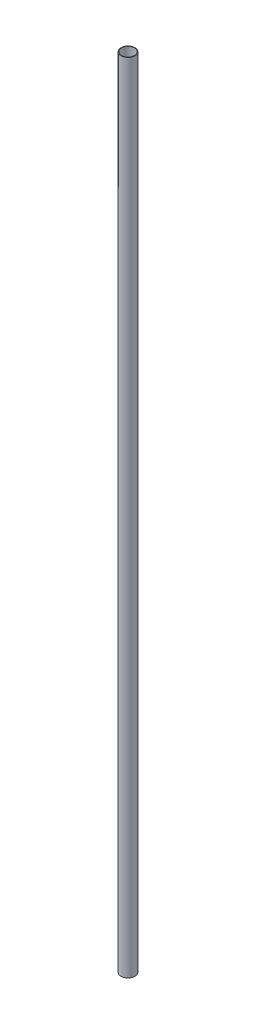
SolidWorks part; units mm, degrees
ref_plane "Front Plane" through (0, 0, 0) normal (0, 0, 1) x (1, 0, 0)
ref_plane "Top Plane" through (0, 0, 0) normal (0, 1, 0) x (1, 0, 0)
ref_plane "Right Plane" through (0, 0, 0) normal (1, 0, 0) x (0, 0, -1)
sketch "Sketch1" plane through (0, 0, 0) normal (0, 1, 0) x (1, 0, 0)
  circle A0 centre (0, 0) radius 7.5
  dimension "D1" = 15
extrude "Boss-Extrude1" add sketch "Sketch1" against normal blind 857
sketch "Sketch2" plane through (0, 0, 0) normal (0, 1, 0) x (1, 0, 0)
  circle A0 centre (0, 0) radius 7
  dimension "D1" = 14
extrude "Cut-Extrude1" cut sketch "Sketch2" against normal through all
